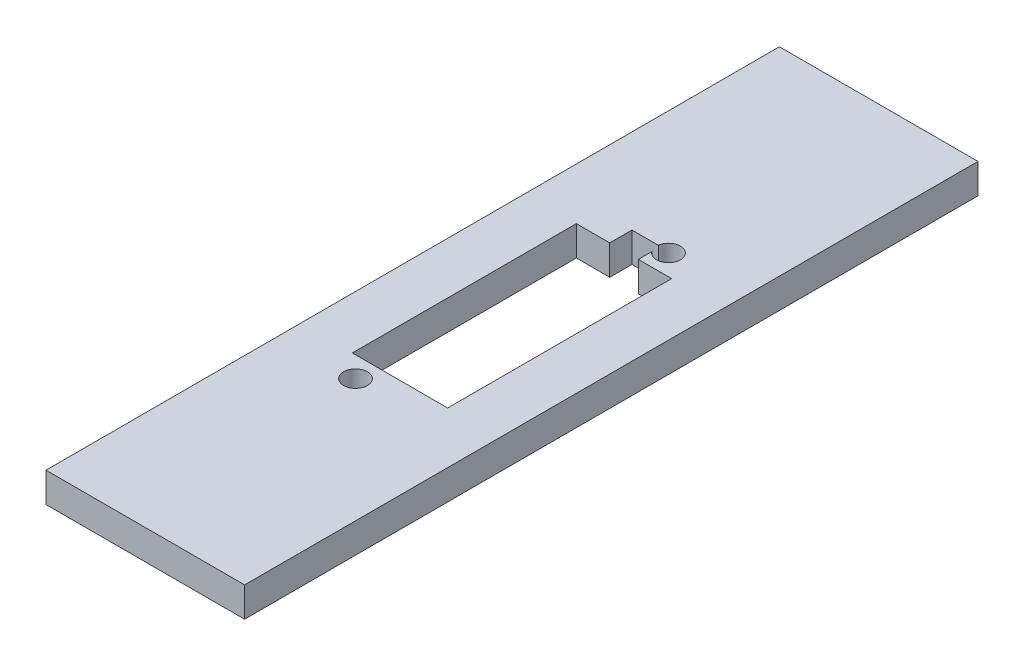
SolidWorks part; units mm, degrees
material "Cedar"
ref_plane "Front Plane" through (0, 0, 0) normal (0, 0, 1) x (1, 0, 0)
ref_plane "Top Plane" through (0, 0, 0) normal (0, 1, 0) x (1, 0, 0)
ref_plane "Right Plane" through (0, 0, 0) normal (1, 0, 0) x (0, 0, -1)
sketch "Sketch1" plane through (0, 0, 0) normal (0, 1, 0) x (1, 0, 0)
  line L1 (-15.875, 58.6232) -> (15.875, 58.6232)
  line L2 (-15.875, 58.6232) -> (-15.875, -58.6232)
  line L3 (-15.875, -58.6232) -> (15.875, -58.6232)
  line L4 (15.875, 58.6232) -> (15.875, -58.6232)
  line L5 (-15.875, 58.6232) -> (15.875, -58.6232) construction
  line L6 (-15.875, -58.6232) -> (15.875, 58.6232) construction
  point P0 (0, 0)
  dimension "D1" = 117.2464
  dimension "D2" = 31.75
extrude "Boss-Extrude1" add sketch "Sketch1" along normal blind 4.7625
sketch "Sketch3" plane through (0, 4.7625, 0) normal (0, 1, 0) x (1, 0, 0)
  line L1 (-7.62, 17.907) -> (7.62, 17.907)
  line L2 (-7.62, 17.907) -> (-7.62, -17.907)
  line L3 (-7.62, -17.907) -> (7.62, -17.907)
  line L4 (7.62, 17.907) -> (7.62, -17.907)
  line L5 (-7.62, 17.907) -> (7.62, -17.907) construction
  line L6 (-7.62, -17.907) -> (7.62, 17.907) construction
  point P0 (0, 0)
  dimension "D1" = 15.24
  dimension "D2" = 35.814
extrude "Cut-Extrude1" cut sketch "Sketch3" against normal up to surface (4.7625 mm away) up to face at (0, 0, 0)
sketch "Sketch4" plane through (0, 4.7625, 0) normal (0, 1, 0) x (1, 0, 0)
  line L2 (0, 17.907) -> (0, 22.987) construction
  line L3 (0, 58.6232) -> (0, 17.907) construction
  line L4 (15.875, 58.6232) -> (-15.875, 58.6232) construction
  line L6 (7.62, 17.907) -> (-7.62, 17.907) construction
  line L17 (-2.286, 17.907) -> (2.286, 17.907)
  line L18 (-2.286, 21.463) -> (2.286, 21.463)
  line L19 (-2.286, 21.463) -> (-2.286, 17.907)
  line L21 (2.286, 21.463) -> (2.286, 17.907)
  line L22 (-2.286, 21.463) -> (0, 17.907) construction
  line L23 (0, 17.907) -> (2.286, 21.463) construction
  circle A0 centre (-3.81, -21.209) radius 1.905
  circle A2 centre (3.81, 21.209) radius 1.905
  point P5 (0, 17.907)
  point P7 (0, 17.907)
  point P15 (0, 17.907)
  line M7 (-7.62, 17.907) -> (7.62, 17.907)
  dimension "D1" = 4.572
  dimension "D2" = 3.556
  dimension "D3" = 3.81
  dimension "D4" = 0.254
extrude "Cut-Extrude9" cut sketch "Sketch4" against normal up to surface (4.7625 mm away) contours A0 | A2 L18 L19 L21 M7 | L21 A2 L18 up to face at (0, 0, 0)
